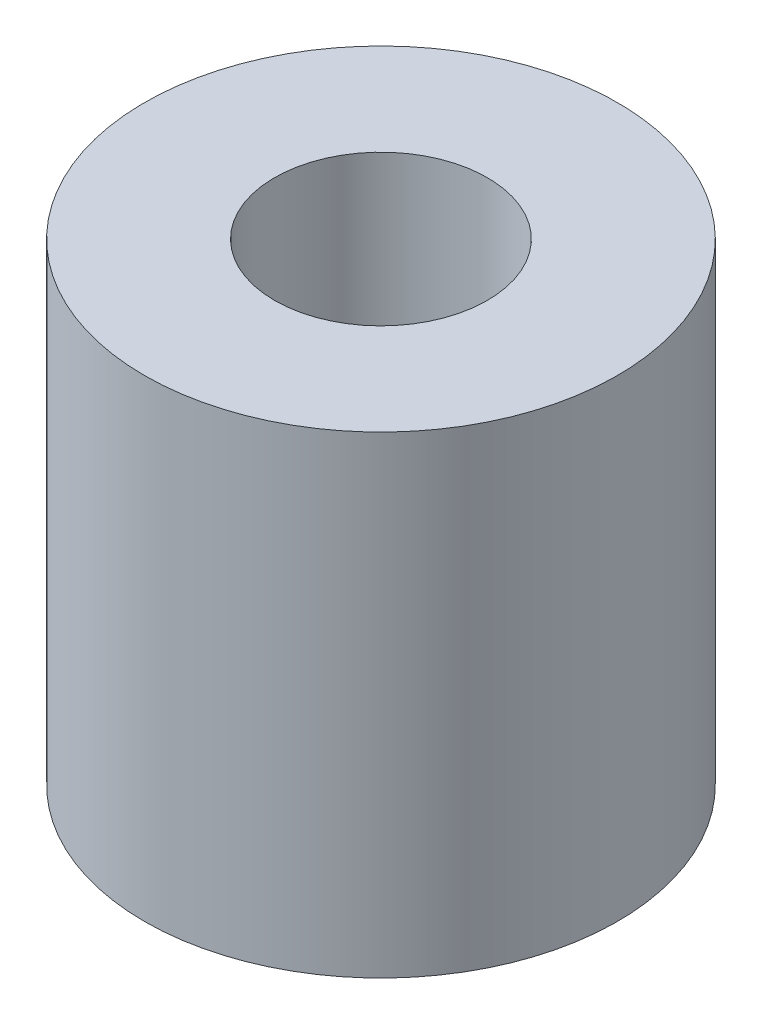
SolidWorks part; units mm, degrees
ref_plane "Front Plane" through (0, 0, 0) normal (0, 0, 1) x (1, 0, 0)
ref_plane "Top Plane" through (0, 0, 0) normal (0, 1, 0) x (1, 0, 0)
ref_plane "Right Plane" through (0, 0, 0) normal (1, 0, 0) x (0, 0, -1)
sketch "Sketch1" plane through (0, 0, 0) normal (0, 1, 0) x (1, 0, 0)
  circle A0 centre (0, 0) radius 4.5
  circle A1 centre (0, 0) radius 10
  dimension "D1" = 20
  dimension "D2" = 9
extrude "Boss-Extrude1" add sketch "Sketch1" along normal blind 20
sketch "Sketch2" plane through (0, 0, 0) normal (0, -1, 0) x (1, 0, 0)
  line L0 (-10, 0) -> (-4.5, 0) construction
  circle A0 centre (0, 0) radius 10 construction
  circle A1 centre (0, 0) radius 4.5 construction
  circle A2 centre (-7.25, 0) radius 1
  circle A3 centre (-6.532, 3.1457) radius 1
  circle A4 centre (-4.5203, 5.6683) radius 1
  circle A5 centre (-1.6133, 7.0682) radius 1
  circle A6 centre (1.6133, 7.0682) radius 1
  circle A7 centre (4.5203, 5.6683) radius 1
  circle A8 centre (6.532, 3.1457) radius 1
  circle A9 centre (7.25, 0) radius 1
  circle A10 centre (6.532, -3.1457) radius 1
  circle A11 centre (4.5203, -5.6683) radius 1
  circle A12 centre (1.6133, -7.0682) radius 1
  circle A13 centre (-1.6133, -7.0682) radius 1
  circle A14 centre (-4.5203, -5.6683) radius 1
  circle A15 centre (-6.532, -3.1457) radius 1
  point P37 (0, 0)
  dimension "D1" = 2
  dimension "D2" = 14
extrude "Cut-Extrude1" cut sketch "Sketch2" against normal blind 2
